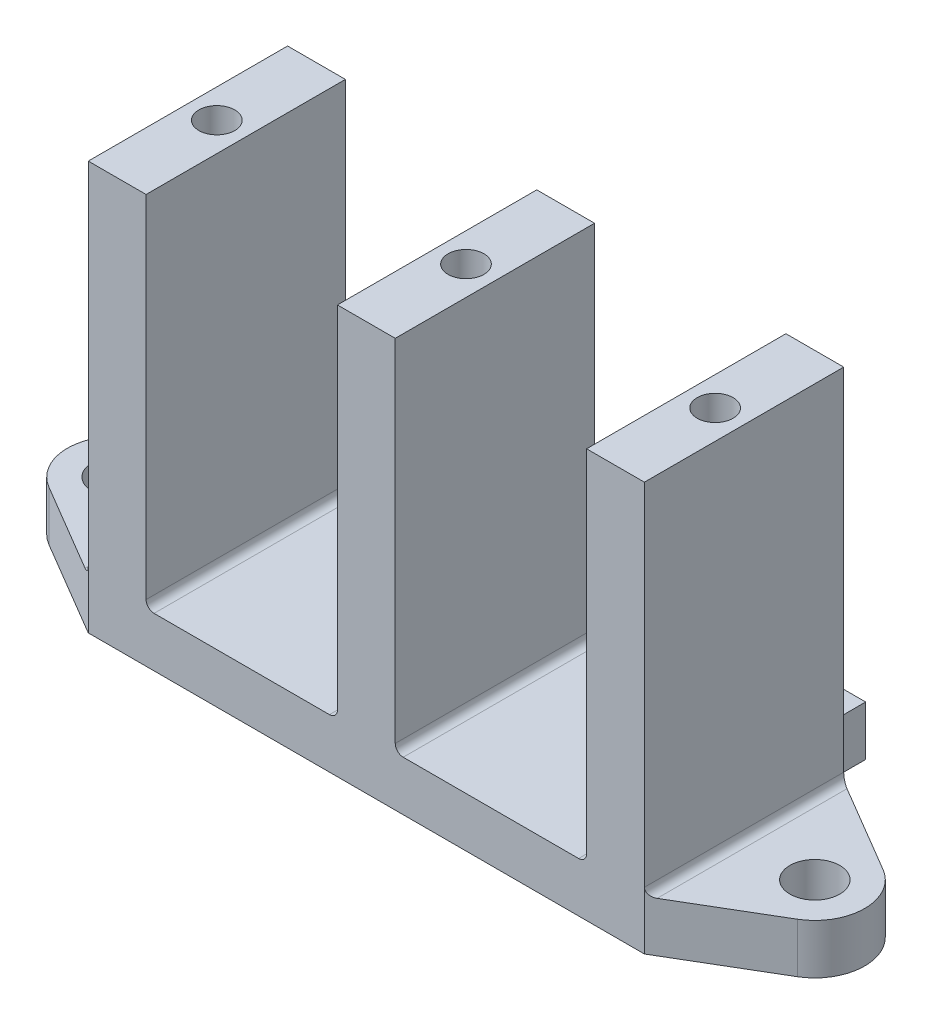
SolidWorks part; units mm, degrees
ref_plane "Front Plane" through (0, 0, 0) normal (0, 0, 1) x (1, 0, 0)
ref_plane "Top Plane" through (0, 0, 0) normal (0, 1, 0) x (1, 0, 0)
ref_plane "Right Plane" through (0, 0, 0) normal (1, 0, 0) x (0, 0, -1)
sketch "Sketch1" plane through (0, 0, 0) normal (0, 1, 0) x (1, 0, 0)
  line L0 (-14.0335, -6.35) -> (-1.8415, -6.35) construction
  line L5 (-1.8415, -6.35) -> (1.8415, -6.35)
  line L6 (-1.8415, -6.35) -> (-1.8415, 6.35)
  line L7 (-1.8415, 6.35) -> (1.8415, 6.35)
  line L8 (1.8415, -6.35) -> (1.8415, 6.35)
  line L9 (-1.8415, -6.35) -> (1.8415, 6.35) construction
  line L10 (-1.8415, 6.35) -> (1.8415, -6.35) construction
  line L11 (-17.7165, -6.35) -> (-14.0335, -6.35)
  line L12 (-17.7165, -6.35) -> (-17.7165, 6.35)
  line L13 (-17.7165, 6.35) -> (-14.0335, 6.35)
  line L14 (-14.0335, -6.35) -> (-14.0335, 6.35)
  line L15 (-17.7165, -6.35) -> (-14.0335, 6.35) construction
  line L16 (-17.7165, 6.35) -> (-14.0335, -6.35) construction
  line L17 (14.0335, -6.35) -> (17.7165, -6.35)
  line L18 (14.0335, -6.35) -> (14.0335, 6.35)
  line L19 (14.0335, 6.35) -> (17.7165, 6.35)
  line L20 (17.7165, -6.35) -> (17.7165, 6.35)
  line L21 (14.0335, -6.35) -> (17.7165, 6.35) construction
  line L22 (14.0335, 6.35) -> (17.7165, -6.35) construction
  line L23 (1.8415, -6.35) -> (14.0335, -6.35) construction
  line L24 (-7.9375, -6.35) -> (-7.9375, -22.225) construction
  line L25 (-7.9375, -22.225) -> (7.9375, -22.225) construction
  line L26 (7.9375, -22.225) -> (7.9375, -6.35) construction
  point P0 (0, 0)
  point P6 (-15.875, 0)
  point P12 (15.875, 0)
  dimension "D1" = 12.192
  dimension "D2" = 15.875
  dimension "D3" = 12.7
extrude "Boss-Extrude1" add sketch "Sketch1" along normal blind 22.86
sketch "Sketch2" plane through (0, 0, 0) normal (0, 1, 0) x (1, 0, 0)
  line L0 (-23.8396, -2.7338) -> (-17.7165, -6.35)
  line L1 (-17.7165, 6.35) -> (17.7165, 6.35)
  line L2 (-17.7165, 6.35) -> (-17.7165, -6.35) construction
  line L3 (-17.7165, -6.35) -> (17.7165, -6.35)
  line L4 (17.7165, 6.35) -> (17.7165, -6.35)
  line L5 (-17.7165, 6.35) -> (17.7165, -6.35) construction
  line L6 (-17.7165, -6.35) -> (17.7165, 6.35) construction
  line L7 (-23.8396, 2.7338) -> (-17.7165, 6.35)
  circle A0 centre (-22.225, 0) radius 1.5875
  arc A1 (-23.8396, -2.7338) -> (-23.8396, 2.7338) centre (-22.225, 0) cw
  point P0 (0, 0)
  dimension "D2" = 3.175
  dimension "D3" = 1.5875
  dimension "D1" = 22.225
extrude "Boss-Extrude2" add sketch "Sketch2" against normal blind 3.175
mirror "Mirror1" about plane through (0, 0, 0) normal (1, 0, 0) of "Boss-Extrude2"
fillet "Fillet1" radius 0.508 6 edges at (-17.7165, 0, 0) (-1.8415, 0, 0) (14.0335, 0, 0) (17.7165, 0, 0) (-14.0335, 0, 0) (1.8415, 0, 0)
sketch "Sketch3" plane through (0, 22.86, 0) normal (0, 1, 0) x (1, 0, 0)
  line L0 (-17.7165, 6.35) -> (-14.0335, -6.35) construction
  line L1 (-1.8415, 6.35) -> (1.8415, -6.35) construction
  line L2 (14.0335, 6.35) -> (17.7165, -6.35) construction
  line L3 (-1.8415, 6.35) -> (-1.8415, -6.35) construction
  circle A0 centre (15.875, 0) radius 1.143
  circle A1 centre (0, 0) radius 1.143
  circle A2 centre (-15.875, 0) radius 1.143
  dimension "D1" = 2.286
extrude "Cut-Extrude1" cut sketch "Sketch3" against normal blind 12.7
sketch "Sketch4" plane through (0, 0, -6.35) normal (0, 0, -1) x (-1, 0, 0)
  line L0 (-14.0335, -3.175) -> (-1.8415, 0) construction
  line L1 (-14.0335, 22.86) -> (-14.0335, 0.508) construction
  line L3 (-1.8415, 22.86) -> (-1.8415, 0.508) construction
  line L4 (17.7165, -3.175) -> (-17.7165, -3.175) construction
  line L5 (-13.5255, 0) -> (-2.3495, 0) construction
  line L6 (-14.0335, 0) -> (-1.8415, 0)
  line L7 (-14.0335, 0) -> (-14.0335, -3.175)
  line L8 (-14.0335, -3.175) -> (-1.8415, -3.175)
  line L9 (-1.8415, 0) -> (-1.8415, -3.175)
extrude "Boss-Extrude3" add sketch "Sketch4" along normal blind 5.08
fillet "Fillet2" radius 1.5875 2 edges at (14.0335, -1.5875, -6.35) (1.8415, -1.5875, -6.35)
